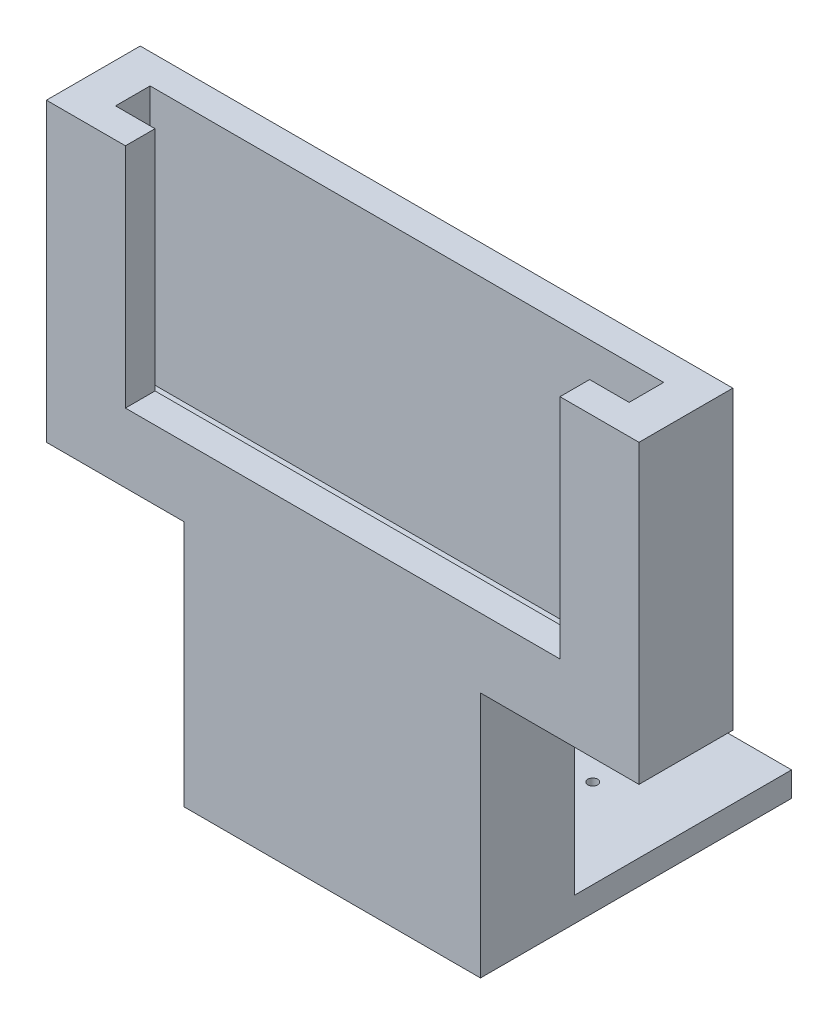
SolidWorks part; units mm, degrees
ref_plane "Plan de face" through (0, 0, 0) normal (0, 0, 1) x (1, 0, 0)
ref_plane "Plan de dessus" through (0, 0, 0) normal (0, 1, 0) x (1, 0, 0)
ref_plane "Plan de droite" through (0, 0, 0) normal (1, 0, 0) x (0, 0, -1)
sketch "Esquisse1" plane through (0, 0, 0) normal (0, 0, 1) x (1, 0, 0)
  line L1 (30, -15) -> (-30, -15)
  line L2 (30, -15) -> (30, 15)
  line L3 (30, 15) -> (-30, 15)
  line L4 (-30, -15) -> (-30, 15)
  line L5 (30, -15) -> (-30, 15) construction
  line L6 (30, 15) -> (-30, -15) construction
  line L7 (13.951, -40) -> (-16.049, -40)
  line L8 (13.951, -40) -> (13.951, -15)
  line L9 (13.951, -15) -> (-16.049, -15)
  line L10 (-16.049, -40) -> (-16.049, -15)
  line L11 (13.951, -40) -> (-16.049, -15) construction
  line L12 (13.951, -15) -> (-16.049, -40) construction
  point P0 (0, 0)
  point P6 (-1.049, -27.5)
  dimension "D1" = 60
  dimension "D2" = 30
  dimension "D3" = 30
  dimension "D4" = 25
extrude "Boss.-Extru.1" add sketch "Esquisse1" along normal blind 3 contours L4 L1 L2 L3 | L10 L7 L8 L1
sketch "Esquisse2" plane through (0, 0, 3) normal (0, 0, 1) x (1, 0, 0)
  line L0 (30, -15) -> (13.951, -15) construction
  line L1 (-30, 15) -> (-26, 15)
  line L2 (-30, 15) -> (-30, -15)
  line L3 (-30, -15) -> (-26, -15)
  line L4 (-26, 15) -> (-26, -15)
  line L5 (30, 15) -> (26, 15)
  line L6 (30, 15) -> (30, -15)
  line L7 (30, -15) -> (26, -15)
  line L8 (26, 15) -> (26, -15)
  line L10 (-26, -15) -> (26, -15)
  line L11 (-26, -15) -> (-26, -11)
  line L12 (-26, -11) -> (26, -11)
  line L13 (26, -15) -> (26, -11)
  line L14 (-16.049, -40) -> (13.951, -40)
  line L15 (-16.049, -40) -> (-16.049, -15)
  line L16 (-16.049, -15) -> (13.951, -15)
  line L17 (13.951, -40) -> (13.951, -15)
  dimension "D1" = 4
  dimension "D2" = 4
  dimension "D3" = 4
extrude "Boss.-Extru.2" add sketch "Esquisse2" along normal blind 3.5 contours L2 L1 L4 L3 | L11 L10 L13 L12 | L6 L5 L8 L7 | L15 L14 L17 L16
sketch "Esquisse3" plane through (0, 0, 6.5) normal (0, 0, 1) x (1, 0, 0)
  line L0 (-30, -15) -> (-16.049, -15) construction
  line L1 (-30, 15) -> (-22, 15)
  line L2 (-30, 15) -> (-30, -15)
  line L3 (-30, -15) -> (-22, -15)
  line L4 (-22, 15) -> (-22, -15)
  line L5 (26, 15) -> (-26, 15) construction
  line L6 (30, -15) -> (22, -15)
  line L7 (30, -15) -> (30, 15)
  line L8 (30, 15) -> (22, 15)
  line L9 (22, -15) -> (22, 15)
  line L10 (13.951, -40) -> (13.951, -15) construction
  line L11 (-22, -15) -> (22, -15)
  line L12 (-22, -15) -> (-22, -8)
  line L13 (-22, -8) -> (22, -8)
  line L14 (22, -15) -> (22, -8)
  line L15 (-16.049, -15) -> (13.951, -15)
  line L16 (-16.049, -15) -> (-16.049, -40)
  line L17 (-16.049, -40) -> (13.951, -40)
  line L18 (13.951, -15) -> (13.951, -40)
  dimension "D1" = 8
  dimension "D2" = 8
  dimension "D3" = 7
extrude "Boss.-Extru.3" add sketch "Esquisse3" along normal blind 3 contours L2 L1 L4 L3 | L12 L11 L14 L13 | L7 L6 L9 L8 | L16 L15 L18 L17
sketch "Esquisse4" plane through (0, 0, 0) normal (0, 0, -1) x (-1, 0, 0)
  line L0 (16.049, -40) -> (16.049, -15) construction
  line L1 (-13.951, -40) -> (16.049, -40)
  line L2 (-13.951, -40) -> (-13.951, -37.5)
  line L3 (-13.951, -37.5) -> (16.049, -37.5)
  line L4 (16.049, -40) -> (16.049, -37.5)
  dimension "D1" = 2.5
extrude "Boss.-Extru.4" add sketch "Esquisse4" along normal blind 22
sketch "Esquisse6" plane through (0, -40, 0) normal (0, -1, 0) x (1, 0, 0)
  line L0 (-1.049, -22) -> (-1.049, 12.4625) construction
  line L1 (13.951, -22) -> (-16.049, -22) construction
  line L2 (-18.3694, -10.8684) -> (22.7394, -10.8684) construction
  circle A0 centre (-1.049, -10.8684) radius 3
  dimension "D1" = 6
extrude "Enlèv. mat.-Extru.1" cut sketch "Esquisse6" against normal blind 1.5
sketch "Esquisse7" plane through (0, -38.5, 0) normal (0, -1, 0) x (1, 0, 0)
  circle A0 centre (-1.049, -10.8684) radius 1.5
  dimension "D1" = 3
extrude "Enlèv. mat.-Extru.2" cut sketch "Esquisse7" against normal blind 6
sketch "Esquisse8" plane through (0, -40, 0) normal (0, -1, 0) x (1, 0, 0)
  line L0 (-1.049, -24.3849) -> (-1.049, 14.7213) construction
  line L1 (-1.049, -10.8684) -> (-19.9152, -10.8684) construction
  line L2 (-19.9152, -10.8684) -> (22.2688, -10.8684) construction
  circle A0 centre (-1.049, -4.8684) radius 0.5
  circle A1 centre (-1.049, -16.8684) radius 0.5
  circle A2 centre (4.951, -10.8684) radius 0.5
  circle A3 centre (-7.049, -10.8684) radius 0.5
  circle A4 centre (-1.049, -10.8684) radius 3 construction
  circle A5 centre (-1.049, -10.8684) radius 3 construction
  dimension "D1" = 1
  dimension "D2" = 1
  dimension "D3" = 1
  dimension "D4" = 1
  dimension "D5" = 6
  dimension "D6" = 6
  dimension "D7" = 6
  dimension "D8" = 6
extrude "Enlèv. mat.-Extru.3" cut sketch "Esquisse8" against normal blind 10
